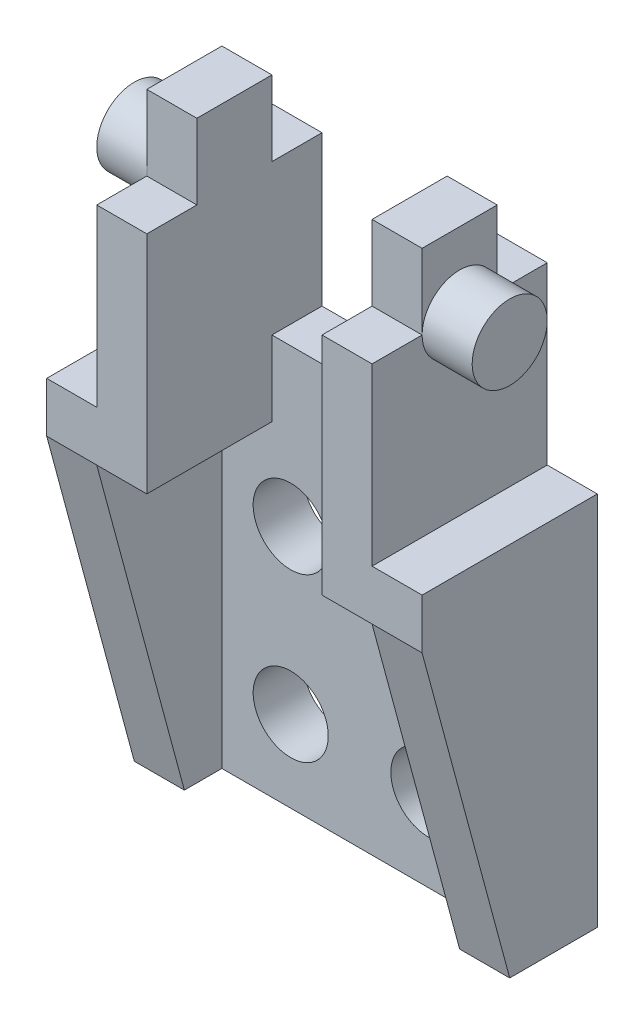
SolidWorks part; units mm, degrees
ref_plane "Спереди" through (0, 0, 0) normal (0, 0, 1) x (1, 0, 0)
ref_plane "Сверху" through (0, 0, 0) normal (0, 1, 0) x (1, 0, 0)
ref_plane "Справа" through (0, 0, 0) normal (1, 0, 0) x (0, 0, -1)
sketch "Эскиз1" plane through (0, 0, 0) normal (0, 0, 1) x (1, 0, 0)
  line L1 (-7.5, 12.5) -> (7.5, 12.5)
  line L2 (-7.5, 12.5) -> (-7.5, -12.5)
  line L3 (-7.5, -12.5) -> (7.5, -12.5)
  line L4 (7.5, 12.5) -> (7.5, -12.5)
  line L5 (-7.5, 12.5) -> (7.5, -12.5) construction
  line L6 (-7.5, -12.5) -> (7.5, 12.5) construction
  point P0 (0, 0)
  dimension "D1" = 15
  dimension "D2" = 25
extrude "Бобышка-Вытянуть1" add sketch "Эскиз1" along normal blind 7
sketch "Эскиз2" plane through (0, 0, 7) normal (0, 0, 1) x (1, 0, 0)
  line L0 (-7.5, 12.5) -> (-5.5, 12.5)
  line L1 (7.5, 12.5) -> (-7.5, 12.5) construction
  line L2 (-5.5, 12.5) -> (-5.5, -12.5)
  line L3 (-7.5, -12.5) -> (7.5, -12.5) construction
  line L4 (-5.5, -12.5) -> (5.5, -12.5)
  line L5 (5.5, -12.5) -> (5.5, 12.5)
  line L6 (5.5, 12.5) -> (7.5, 12.5)
  line L7 (7.5, 12.5) -> (-7.5, 12.5)
  line L8 (-5.5, -12.5) -> (-5.5, 0.5)
  line L9 (-5.5, 0.5) -> (-3.5, 0.5)
  line L10 (-3.5, 0.5) -> (-3.5, 12.5)
  line L11 (-3.5, 12.5) -> (3.5, 12.5)
  line L12 (3.5, 12.5) -> (5.5, 12.5)
  line L13 (3.5, 12.5) -> (3.5, 0.5)
  line L14 (3.5, 0.5) -> (5.5, 0.5)
  line M6 (-7.5, -12.5) -> (7.5, -12.5)
  dimension "D1" = 2
  dimension "D2" = 2
  dimension "D3" = 12
extrude "Вырез-Вытянуть1" cut sketch "Эскиз2" against normal blind 5 contours L14 L13 L7 L10 L9 L2 L5 M6
sketch "Эскиз3" plane through (0, 0, 7) normal (0, 0, 1) x (1, 0, 0)
  line L0 (-7.5, 12.5) -> (-5.5, 12.5)
  line L1 (-3.5, 12.5) -> (-7.5, 12.5) construction
  line L2 (-5.5, 12.5) -> (-5.5, 2.5)
  line L3 (-5.5, 2.5) -> (-7.5, 2.5)
  line L4 (-7.5, 12.5) -> (-7.5, -12.5) construction
  line L5 (-7.5, 2.5) -> (-7.5, 12.5)
  line L6 (0, 13.2014) -> (0, 4.2809)
  line L7 (7.5, 2.5) -> (7.5, 12.5)
  line L8 (5.5, 2.5) -> (7.5, 2.5)
  line L9 (5.5, 12.5) -> (5.5, 2.5)
  line L10 (7.5, 12.5) -> (5.5, 12.5)
  line M5 (7.5, -12.5) -> (7.5, 12.5)
  line M6 (7.5, 12.5) -> (3.5, 12.5)
  dimension "D1" = 10
extrude "Вырез-Вытянуть2" cut sketch "Эскиз3" against normal blind 13 contours L5 L3 L2 L0 | L9 L8 M6 M5
sketch "Эскиз4" plane through (-5.5, 0, 0) normal (-1, 0, 0) x (0, 0, 1)
  line L0 (7, 12.5) -> (5, 12.5)
  line L1 (0, 12.5) -> (7, 12.5) construction
  line L2 (5, 12.5) -> (5, 9.5)
  line L3 (5, 9.5) -> (7, 9.5)
  line L4 (7, 12.5) -> (7, 2.5) construction
  line L5 (3.5, 12.5) -> (3.5, 9.5219)
  line L6 (2, 9.5) -> (0, 9.5)
  line L7 (2, 12.5) -> (2, 9.5)
  line L8 (0, 12.5) -> (2, 12.5)
  line L9 (7, 12.5) -> (7, 9.5)
  line L10 (0, 9.5) -> (0, 12.5)
  line M4 (0, 12.5) -> (0, 2.5)
  line M6 (7, 2.5) -> (7, 12.5)
  line M7 (7, 12.5) -> (0, 12.5)
  dimension "D1" = 2
  dimension "D2" = 3
extrude "Вырез-Вытянуть3" cut sketch "Эскиз4" against normal through all contours L2 L3 M6 M7 | L7 L6 M7 M4
sketch "Эскиз5" plane through (0, 0, 2) normal (0, 0, 1) x (1, 0, 0)
  line L0 (-3.5, 0.5) -> (-3.5, 9.5) construction
  line L1 (3.5, 9.5) -> (-3.5, 9.5)
  line L2 (3.5, 9.5) -> (3.5, 3.5)
  line L3 (3.5, 3.5) -> (-3.5, 3.5)
  line L4 (-3.5, 9.5) -> (-3.5, 3.5)
  dimension "D1" = 6
extrude "Вырез-Вытянуть4" cut sketch "Эскиз5" against normal blind 13
sketch "Эскиз6" plane through (-5.5, 0, 0) normal (-1, 0, 0) x (0, 0, 1)
  line L0 (5, 9.5) -> (3.5, 9.5)
  circle A0 centre (3.5, 9.5) radius 1.5
  dimension "D1" = 3
extrude "Бобышка-Вытянуть2" add sketch "Эскиз6" along normal blind 2
sketch "Эскиз7" plane through (5.5, 0, 0) normal (1, 0, 0) x (0, 0, -1)
  line L0 (-2, 9.5) -> (-3.5, 9.5)
  circle A0 centre (-3.5, 9.5) radius 1.5
  dimension "D1" = 3
extrude "Бобышка-Вытянуть3" add sketch "Эскиз7" along normal blind 2
sketch "Эскиз8" plane through (-7.5, 0, 0) normal (-1, 0, 0) x (0, 0, 1)
  line L0 (7, 0.5) -> (3.5, -12.5)
  line L1 (7, -12.5) -> (0, -12.5) construction
  line L2 (3.5, -12.5) -> (7, -12.5)
  line L3 (7, -12.5) -> (7, 0.5)
extrude "Вырез-Вытянуть5" cut sketch "Эскиз8" against normal through all
sketch "Эскиз9" plane through (0, 0, 2) normal (0, 0, 1) x (1, 0, 0)
  line L1 (5.5, -12.5) -> (5.5, 0.5)
  circle A0 centre (-2.75, -2.75) radius 1.5
  circle A1 centre (-2.75, -9.25) radius 1.5
  circle A2 centre (2.75, -2.75) radius 1.5
  circle A3 centre (2.75, -9.25) radius 1.5
  dimension "D1" = 3
extrude "Вырез-Вытянуть6" cut sketch "Эскиз9" against normal through all contours A0 | A2 | A1 | A3
